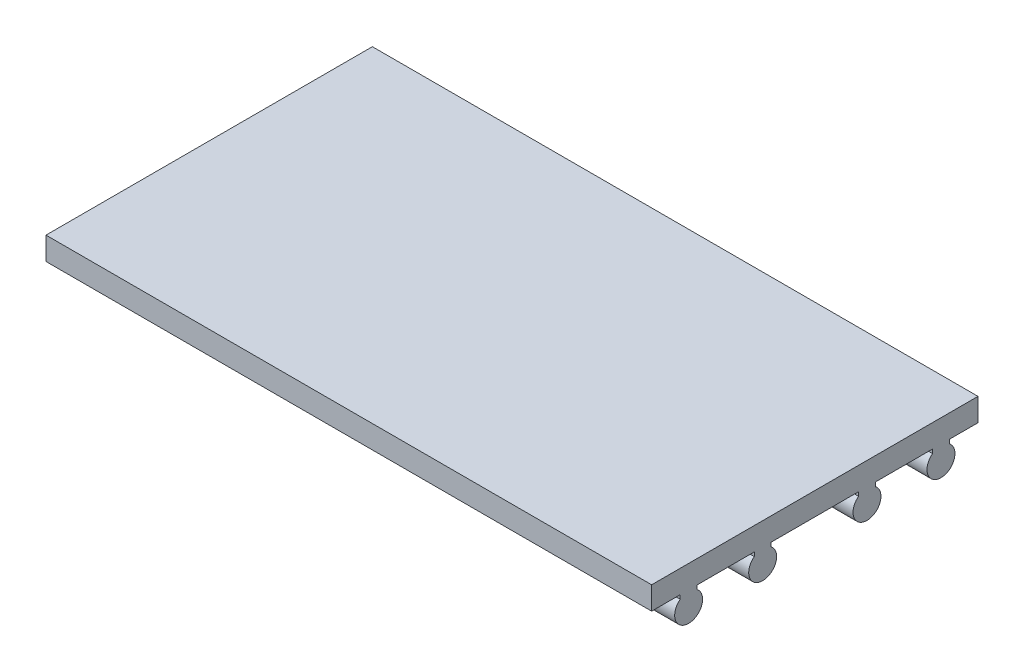
SolidWorks part; units mm, degrees
ref_plane "Спереди" through (0, 0, 0) normal (0, 0, 1) x (1, 0, 0)
ref_plane "Сверху" through (0, 0, 0) normal (0, 1, 0) x (1, 0, 0)
ref_plane "Справа" through (0, 0, 0) normal (1, 0, 0) x (0, 0, -1)
ref_plane "Плоскость4" through (90, 0, 0) normal (1, 0, 0) x (0, 0, -1)
sketch "Эскиз1" plane through (90, 0, 0) normal (1, 0, 0) x (0, 0, -1)
  line L0 (6.75, 225.9062) -> (6.75, 320.75)
  line L1 (6.75, 320.75) -> (-38.0938, 320.75)
  line L2 (-38.0938, 318.25) -> (-37.5, 318.25)
  line L3 (-37.5, 318.25) -> (-37.5, 284.75)
  line L4 (-37.5, 284.75) -> (-38.0938, 284.75)
  line L5 (-38.0938, 282.25) -> (-37.5, 282.25)
  line L6 (-37.5, 282.25) -> (-37.5, 269.25)
  line L7 (-37.5, 269.25) -> (-38.0938, 269.25)
  line L8 (-38.0938, 266.75) -> (-37.5, 266.75)
  line L9 (-37.5, 266.75) -> (-37.5, 233.25)
  line L10 (-37.5, 233.25) -> (-38.0938, 233.25)
  line L11 (-38.0938, 230.75) -> (-37.5, 230.75)
  line L12 (-37.5, 230.75) -> (-37.5, 226.5)
  line L13 (-37.5, 226.5) -> (-33.25, 226.5)
  line L14 (-33.25, 226.5) -> (-33.25, 225.9062)
  line L15 (-30.75, 225.9062) -> (-30.75, 226.5)
  line L16 (-30.75, 226.5) -> (-22.25, 226.5)
  line L17 (-22.25, 226.5) -> (-22.25, 225.9062)
  line L18 (-19.75, 225.9062) -> (-19.75, 226.5)
  line L19 (-19.75, 226.5) -> (-6.75, 226.5)
  line L20 (-6.75, 226.5) -> (-6.75, 225.9062)
  line L21 (-4.25, 225.9062) -> (-4.25, 226.5)
  line L22 (-4.25, 226.5) -> (4.25, 226.5)
  line L23 (4.25, 226.5) -> (4.25, 225.9062)
  arc A0 (-38.0938, 320.75) -> (-38.0938, 318.25) centre (-39.75, 319.5) ccw
  arc A1 (-38.0938, 284.75) -> (-38.0938, 282.25) centre (-39.75, 283.5) ccw
  arc A2 (-38.0938, 269.25) -> (-38.0938, 266.75) centre (-39.75, 268) ccw
  arc A3 (-38.0938, 233.25) -> (-38.0938, 230.75) centre (-39.75, 232) ccw
  arc A4 (-33.25, 225.9062) -> (-30.75, 225.9062) centre (-32, 224.25) ccw
  arc A5 (-22.25, 225.9062) -> (-19.75, 225.9062) centre (-21, 224.25) ccw
  arc A6 (-6.75, 225.9062) -> (-4.25, 225.9062) centre (-5.5, 224.25) ccw
  arc A7 (4.25, 225.9062) -> (6.75, 225.9062) centre (5.5, 224.25) ccw
extrude "Бобышка-Вытянуть1" add sketch "Эскиз1" against normal blind 90
sketch "Эскиз2" plane through (0, 320.75, 0) normal (0, 1, 0) x (-1, 0, 0)
  line L0 (-90, -6.75) -> (-90, 37.5)
  line L1 (-90, 37.5) -> (0, 37.5)
  line L2 (0, 37.5) -> (0, -6.75)
  line L3 (0, -6.75) -> (-90, -6.75)
extrude "Бобышка-Вытянуть2" add sketch "Эскиз2" along normal blind 8.2
sketch "Эскиз3" plane through (0, 0, -6.75) normal (0, 0, -1) x (-1, 0, 0)
  line L0 (-90, 226.5) -> (-90, 328.95)
  line L1 (-90, 328.95) -> (0, 328.95)
  line L2 (0, 328.95) -> (0, 226.5)
  line L3 (0, 226.5) -> (-90, 226.5)
extrude "Бобышка-Вытянуть3" add sketch "Эскиз3" along normal blind 8.2
sketch "Эскиз4" plane through (0, 0, 0) normal (-1, 0, 0) x (0, 0, 1)
  line L0 (24.25, 328.95) -> (24.25, 325)
  line L1 (24.25, 325) -> (28.75, 325)
  line L2 (28.75, 325) -> (28.75, 328.95)
  line L3 (28.75, 328.95) -> (24.25, 328.95)
extrude "Вырез-Вытянуть1" cut sketch "Эскиз4" against normal through all
sketch "Эскиз5" plane through (0, 0, 0) normal (-1, 0, 0) x (0, 0, 1)
  line L0 (37.5, 328.95) -> (35.25, 328.95)
  line L1 (35.25, 328.95) -> (35.25, 325)
  line L2 (35.25, 325) -> (37.5, 325)
  line L3 (37.5, 325) -> (37.5, 328.95)
extrude "Вырез-Вытянуть2" cut sketch "Эскиз5" against normal through all
sketch "Эскиз6" plane through (0, 0, 0) normal (-1, 0, 0) x (0, 0, 1)
  line L0 (-14.95, 226.5) -> (-11, 226.5)
  line L1 (-11, 226.5) -> (-11, 228.75)
  line L2 (-11, 228.75) -> (-14.95, 228.75)
  line L3 (-14.95, 228.75) -> (-14.95, 226.5)
extrude "Вырез-Вытянуть3" cut sketch "Эскиз6" against normal through all
sketch "Эскиз7" plane through (0, 0, 0) normal (-1, 0, 0) x (0, 0, 1)
  line L0 (-14.95, 235.25) -> (-11, 235.25)
  line L1 (-11, 235.25) -> (-11, 264.75)
  line L2 (-11, 264.75) -> (-14.95, 264.75)
  line L3 (-14.95, 264.75) -> (-14.95, 235.25)
extrude "Вырез-Вытянуть4" cut sketch "Эскиз7" against normal through all
sketch "Эскиз8" plane through (0, 0, 0) normal (-1, 0, 0) x (0, 0, 1)
  line L0 (-14.95, 271.25) -> (-11, 271.25)
  line L1 (-11, 271.25) -> (-11, 280.25)
  line L2 (-11, 280.25) -> (-14.95, 280.25)
  line L3 (-14.95, 280.25) -> (-14.95, 271.25)
extrude "Вырез-Вытянуть5" cut sketch "Эскиз8" against normal through all
sketch "Эскиз9" plane through (0, 0, 0) normal (-1, 0, 0) x (0, 0, 1)
  line L0 (-14.95, 286.75) -> (-11, 286.75)
  line L1 (-11, 286.75) -> (-11, 316.25)
  line L2 (-11, 316.25) -> (-14.95, 316.25)
  line L3 (-14.95, 316.25) -> (-14.95, 286.75)
extrude "Вырез-Вытянуть6" cut sketch "Эскиз9" against normal through all
sketch "Эскиз10" plane through (0, 0, 0) normal (-1, 0, 0) x (0, 0, 1)
  line L0 (-14.95, 328.95) -> (-14.95, 322.75)
  line L1 (-14.95, 322.75) -> (-11, 322.75)
  line L2 (-11, 322.75) -> (-11, 328.95)
  line L3 (-11, 328.95) -> (-14.95, 328.95)
extrude "Вырез-Вытянуть7" cut sketch "Эскиз10" against normal through all
sketch "Эскиз11" plane through (0, 0, 0) normal (-1, 0, 0) x (0, 0, 1)
  line L0 (-11, 328.95) -> (-11, 325)
  line L1 (-11, 325) -> (-8.75, 325)
  line L2 (-8.75, 325) -> (-8.75, 328.95)
  line L3 (-8.75, 328.95) -> (-11, 328.95)
extrude "Вырез-Вытянуть8" cut sketch "Эскиз11" against normal through all
sketch "Эскиз12" plane through (0, 0, 0) normal (-1, 0, 0) x (0, 0, 1)
  line L0 (-2.25, 328.95) -> (-2.25, 325)
  line L1 (-2.25, 325) -> (2.25, 325)
  line L2 (2.25, 325) -> (2.25, 328.95)
  line L3 (2.25, 328.95) -> (-2.25, 328.95)
extrude "Вырез-Вытянуть9" cut sketch "Эскиз12" against normal through all
sketch "Эскиз13" plane through (0, 0, 0) normal (-1, 0, 0) x (0, 0, 1)
  line L0 (8.75, 328.95) -> (8.75, 325)
  line L1 (8.75, 325) -> (17.75, 325)
  line L2 (17.75, 325) -> (17.75, 328.95)
  line L3 (17.75, 328.95) -> (8.75, 328.95)
extrude "Вырез-Вытянуть10" cut sketch "Эскиз13" against normal through all
sketch "Эскиз14" plane through (90, 0, 0) normal (1, 0, 0) x (0, 0, -1)
  line L0 (9.6, 323.6) -> (-36.1, 323.6)
  line L1 (-36.1, 323.6) -> (-36.1, 227.9)
  line L2 (-36.1, 227.9) -> (9.6, 227.9)
  line L3 (9.6, 227.9) -> (9.6, 323.6)
extrude "Вырез-Вытянуть11" cut sketch "Эскиз14" against normal blind 86
hole_wizard "Диаметр отверстия Ø2.5 (2.5)1" positions "Эскиз16" profile "Эскиз15" hole size "Ø2.5" standard "Ansi Metric"
sketch "Эскиз16" plane through (90, 0, 0) normal (1, 0, 0) x (0, 0, -1)
  point P0 (-39.75, 232)
  point P1 (-21, 224.25)
  point P2 (-39.75, 283.5)
  point P3 (-5.5, 224.25)
  point P4 (5.5, 224.25)
  point P5 (-39.75, 319.5)
  point P6 (-39.75, 268)
  point P7 (-32, 224.25)
sketch "Эскиз15" plane through (90, 232, 39.75) normal (0, 1, 0) x (0, 0, -1)
  line L0 (0, 0) -> (0, 90)
  line L1 (0, 90) -> (1.25, 90)
  line L2 (1.25, 90) -> (1.25, 0)
  line L5 (1.25, 0) -> (0, 0)
  line L11 (0, -6.35) -> (0, 107.95) construction
  dimension "Диаметр сквозного отверстия" = 2.5
  dimension "Глубина сквозного отверстия" = 90
hole_wizard "Диаметр отверстия Ø4.5 (4.5)1" positions "Эскиз18" profile "Эскиз17" hole size "Ø4.5" standard "Ansi Metric"
sketch "Эскиз18" plane through (0, 0, 0) normal (-1, 0, 0) x (0, 0, 1)
  point P0 (21, 327.25)
  point P1 (32, 327.25)
  point P2 (-13.25, 232)
  point P3 (-13.25, 268)
  point P4 (-13.25, 283.5)
  point P5 (-13.25, 319.5)
  point P6 (-5.5, 327.25)
  point P7 (5.5, 327.25)
sketch "Эскиз17" plane through (0, 327.25, 21) normal (0, 1, 0) x (0, 0, 1)
  line L0 (0, 0) -> (0, 90)
  line L1 (0, 90) -> (2.25, 90)
  line L2 (2.25, 90) -> (2.25, 0)
  line L5 (2.25, 0) -> (0, 0)
  line L11 (0, -6.35) -> (0, 107.95) construction
  dimension "Диаметр сквозного отверстия" = 4.5
  dimension "Глубина сквозного отверстия" = 90
hole_wizard "Диаметр отверстия Ø8.3 (8.3)1" positions "Эскиз20" profile "Эскиз19" hole size "Ø8.3" standard "Ansi Metric"
sketch "Эскиз20" plane through (0, 0, 0) normal (-1, 0, 0) x (0, 0, 1)
  point P0 (13.25, 275.75)
sketch "Эскиз19" plane through (0, 275.75, 13.25) normal (0, 1, 0) x (0, 0, 1)
  line L0 (0, 0) -> (0, 3.2)
  line L1 (0, 3.2) -> (4.15, 3.2)
  line L2 (4.15, 3.2) -> (4.15, 0)
  line L5 (4.15, 0) -> (0, 0)
  line L10 (0, 3.2) -> (-4.15, 3.2) construction
  line L11 (0, -6.35) -> (0, 107.95) construction
  dimension "Диаметр отверстия" = 8.3
  dimension "Глубина отверстия" = 3.2
  dimension "Угол заточки сверла" = 180
sketch "Эскиз21" plane through (0, 0, 0) normal (-1, 0, 0) x (0, 0, 1)
  circle A0 centre (13.25, 275.75) radius 4.15
extrude "Вырез-Вытянуть12" cut sketch "Эскиз21" against normal blind 10
sketch "Эскиз22" plane through (90, 0, 0) normal (1, 0, 0) x (0, 0, -1)
  circle A0 centre (-39.75, 319.5) radius 1.6316
  circle A1 centre (-39.75, 283.5) radius 1.5194
  circle A2 centre (-39.75, 268) radius 1.4876
  circle A3 centre (-39.75, 232) radius 1.5817
  circle A4 centre (-32, 224.25) radius 1.4878
  circle A5 centre (-21, 224.25) radius 1.426
  circle A6 centre (-5.5, 224.25) radius 1.6281
  circle A7 centre (5.5, 224.25) radius 1.5237
extrude "Бобышка-Вытянуть4" add sketch "Эскиз22" against normal blind 90
fillet "Скругление1" radius 2 1 edges at (4, 275.75, -9.6)
fillet "Скругление2" radius 2 1 edges at (4, 275.75, 36.1)
fillet "Скругление3" radius 2 3 edges at (4, 323.6, 13.25) (4.5858, 323.6, -9.0142) (4.5858, 323.6, 35.5142)
fillet "Скругление4" radius 2 3 edges at (4.5858, 227.9, -9.0142) (4, 227.9, 13.25) (4.5858, 227.9, 35.5142)
fillet "Скругление5" radius 2 1 edges at (45, 325, 35.25)
fillet "Скругление6" radius 2 1 edges at (45, 325, 28.75)
fillet "Скругление7" radius 2 1 edges at (45, 325, 24.25)
fillet "Скругление8" radius 2 1 edges at (45, 325, 17.75)
fillet "Скругление9" radius 2 1 edges at (45, 325, 8.75)
fillet "Скругление10" radius 2 1 edges at (45, 325, 2.25)
fillet "Скругление11" radius 2 1 edges at (45, 325, -2.25)
fillet "Скругление12" radius 2 1 edges at (45, 325, -8.75)
fillet "Скругление13" radius 2 1 edges at (45, 322.75, -11)
fillet "Скругление14" radius 2 1 edges at (45, 316.25, -11)
fillet "Скругление15" radius 2 1 edges at (45, 286.75, -11)
fillet "Скругление16" radius 2 1 edges at (45, 280.25, -11)
fillet "Скругление17" radius 2 1 edges at (45, 271.25, -11)
fillet "Скругление18" radius 2 1 edges at (45, 264.75, -11)
fillet "Скругление19" radius 2 1 edges at (45, 235.25, -11)
fillet "Скругление20" radius 2 1 edges at (45, 228.75, -11)
sketch "Эскиз23" plane through (90, 0, 0) normal (1, 0, 0) x (0, 0, -1)
  line L5 (9.6, 227.9) -> (-36.1, 227.9) construction
  line L6 (9.6, 227.9) -> (-36.1, 227.9)
  line L7 (9.6, 227.9) -> (20.5117, 227.9)
  line L8 (20.5117, 227.9) -> (20.5117, 346.8721)
  line L9 (20.5117, 346.8721) -> (-56.1993, 346.8721)
  line L10 (-56.1993, 346.8721) -> (-56.1993, 227.9)
  line L11 (-56.1993, 227.9) -> (-36.1, 227.9)
extrude "Вырез-Вытянуть14" cut sketch "Эскиз23" against normal blind 181
sketch "Эскиз25" plane through (0, 227.9, 0) normal (0, 1, 0) x (1, 0, 0)
  line L4 (90, -37.5) -> (90, 11.3637)
  line L5 (90, 11.3637) -> (0, 11.3637)
  line L6 (0, 11.3637) -> (0, -37.5)
  line L7 (0, -37.5) -> (90, -37.5)
  line L8 (90, -37.5) -> (90, 11.3637)
  line L9 (90, 11.3637) -> (0, 11.3637)
  line L10 (0, 11.3637) -> (0, -37.5)
  line L11 (0, -37.5) -> (90, -37.5)
  dimension "D1" = 0
extrude "Бобышка-Вытянуть6" add sketch "Эскиз25" along normal blind 2
sketch "Эскиз26" plane through (0, 0, 0) normal (-1, 0, 0) x (0, 0, 1)
  line L0 (-11, 229.9) -> (-11, 226.5)
  line L1 (-11.3637, 229.9) -> (37.5, 229.9) construction
  line L2 (-11.3637, 229.9) -> (-11.3637, 227.9) construction
  line L3 (-11.3637, 229.9) -> (-11.3637, 227.9)
  line L4 (-11.3637, 229.9) -> (-11, 229.9)
  arc A0 (-11, 226.75) -> (-11.3637, 227.9) centre (-13, 226.75) ccw construction
  arc A1 (-11, 226.75) -> (-11.3637, 227.9) centre (-13, 226.75) ccw
  point P0 (-11, 226.5)
  line M2 (37.5, 229.9) -> (-11.3637, 229.9)
  line M3 (-11.3637, 229.9) -> (-11.3637, 227.9)
  arc M4 (-11.3637, 227.9) -> (-11, 226.75) centre (-13, 226.75) cw
extrude "Вырез-Вытянуть15" cut sketch "Эскиз26" against normal blind 93 contours L0 M2 M3 M4
